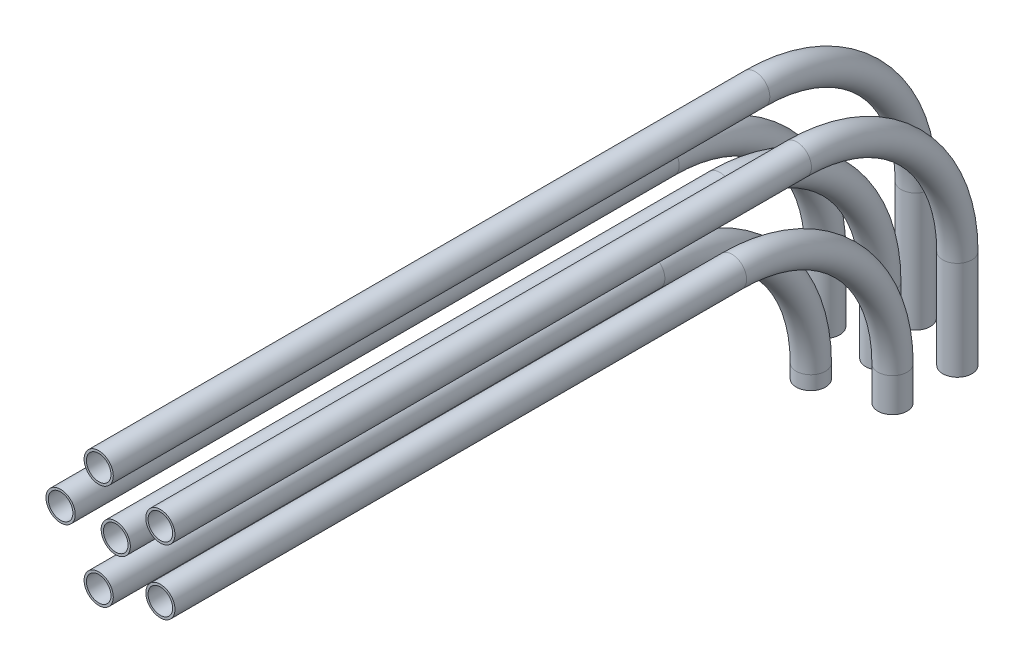
SolidWorks part; units mm, degrees
material "Copper"
ref_plane "Front Plane" through (0, 0, 0) normal (0, 0, 1) x (1, 0, 0)
ref_plane "Top Plane" through (0, 0, 0) normal (0, 1, 0) x (1, 0, 0)
ref_plane "Right Plane" through (0, 0, 0) normal (1, 0, 0) x (0, 0, -1)
sketch "Sketch1" plane through (0, 0, 0) normal (0, 0, 1) x (1, 0, 0)
  line L0 (0, 0) -> (-12, 0) construction
  circle A0 centre (0, 0) radius 3.175
  circle A1 centre (-12, 0) radius 3.175
  circle A2 centre (-3.7082, 11.4127) radius 3.175
  circle A3 centre (9.7082, 7.0534) radius 3.175
  circle A4 centre (9.7082, -7.0534) radius 3.175
  circle A5 centre (-3.7082, -11.4127) radius 3.175
  dimension "D1" = 6.35
  dimension "D2" = 12
  dimension "D3" = 5
extrude "All Tubes Hori" add sketch "Sketch1" along normal blind 120 thin thin type one direction reverse wall 0.5
sketch "Sketch2" plane through (0, 0, 0) normal (0, 0, -1) x (-1, 0, 0)
  line L0 (-6.957, -46.3377) -> (13.6779, -46.3377) construction
  circle A0 centre (3.7082, -11.4127) radius 2.675 construction
  circle A1 centre (3.7082, -11.4127) radius 3.175 construction
  circle A2 centre (3.7082, -11.4127) radius 2.675
  circle A3 centre (3.7082, -11.4127) radius 3.175
  circle A4 centre (-9.7082, -7.0534) radius 3.175 construction
  circle A5 centre (12, 0) radius 3.175 construction
  circle A6 centre (-9.7082, 7.0534) radius 3.175 construction
  dimension "D1" = 31.75
  dimension "D2" = 4.3593
  dimension "D3" = 11.4127
  dimension "D4" = 18.4661
revolve "Tube 1 Revolve" add sketch "Sketch2" angle 90 about L0
sketch "Sketch3" plane through (0, 0, 0) normal (0, 0, -1) x (-1, 0, 0)
  circle A0 centre (-9.7082, -7.0534) radius 2.675 construction
  circle A1 centre (-9.7082, -7.0534) radius 3.175 construction
  circle A2 centre (-9.7082, -7.0534) radius 2.675
  circle A3 centre (-9.7082, -7.0534) radius 3.175
extrude "Tube 2 H Extru" add sketch "Sketch3" along normal blind 4.3593
sketch "Sketch4" plane through (0, 0, -4.3593) normal (0, 0, -1) x (-1, 0, 0)
  line L0 (-15.6235, -41.9784) -> (-3.3734, -41.9784) construction
  circle A0 centre (-9.7082, -7.0534) radius 2.675 construction
  circle A1 centre (-9.7082, -7.0534) radius 3.175 construction
  circle A2 centre (-9.7082, -7.0534) radius 2.675
  circle A3 centre (-9.7082, -7.0534) radius 3.175
  dimension "D1" = 31.75
revolve "Tube 2 Revolve" add sketch "Sketch4" angle 90 about L0
sketch "Sketch5" plane through (0, -41.9784, 0) normal (0, -1, 0) x (1, 0, 0)
  circle A0 centre (9.7082, -39.2843) radius 2.675 construction
  circle A1 centre (9.7082, -39.2843) radius 3.175 construction
  circle A2 centre (9.7082, -39.2843) radius 2.675
  circle A3 centre (9.7082, -39.2843) radius 3.175
extrude "Tube 2 V Extru" add sketch "Sketch5" along normal up to surface (4.3593 mm away) up to face at (-6.3832, -46.3377, -34.925)
sketch "Sketch6" plane through (0, 0, 0) normal (0, 0, -1) x (-1, 0, 0)
  circle A0 centre (12, 0) radius 2.675 construction
  circle A1 centre (12, 0) radius 3.175 construction
  circle A2 centre (0, 0) radius 2.675 construction
  circle A3 centre (0, 0) radius 3.175 construction
  circle A4 centre (12, 0) radius 2.675
  circle A5 centre (12, 0) radius 3.175
  circle A6 centre (0, 0) radius 2.675
  circle A7 centre (0, 0) radius 3.175
extrude "Tube 3 & 4 H Extru" add sketch "Sketch6" along normal blind 11.4127
sketch "Sketch7" plane through (0, 0, -11.4127) normal (0, 0, -1) x (-1, 0, 0)
  line L0 (24.4214, -34.925) -> (-26.0155, -34.925) construction
  circle A0 centre (12, 0) radius 2.675 construction
  circle A1 centre (12, 0) radius 3.175 construction
  circle A2 centre (0, 0) radius 3.175 construction
  circle A3 centre (0, 0) radius 2.675 construction
  circle A4 centre (12, 0) radius 2.675
  circle A5 centre (12, 0) radius 3.175
  circle A6 centre (0, 0) radius 3.175
  circle A7 centre (0, 0) radius 2.675
  dimension "D1" = 31.75
revolve "Tube 3 & 4 Revolve" add sketch "Sketch7" angle 90 about L0
sketch "Sketch8" plane through (0, -34.925, 0) normal (0, -1, 0) x (1, 0, 0)
  circle A0 centre (-12, -46.3377) radius 2.675 construction
  circle A1 centre (-12, -46.3377) radius 3.175 construction
  circle A2 centre (0, -46.3377) radius 3.175 construction
  circle A3 centre (0, -46.3377) radius 2.675 construction
  circle A4 centre (-12, -46.3377) radius 2.675
  circle A5 centre (-12, -46.3377) radius 3.175
  circle A6 centre (0, -46.3377) radius 3.175
  circle A7 centre (0, -46.3377) radius 2.675
extrude "Tube 3 & 4 V Extru" add sketch "Sketch8" along normal up to surface (11.4127 mm away) up to face at (-6.3832, -46.3377, -34.925)
sketch "Sketch9" plane through (0, 0, 0) normal (0, 0, -1) x (-1, 0, 0)
  circle A0 centre (-9.7082, 7.0534) radius 3.175 construction
  circle A1 centre (-9.7082, 7.0534) radius 2.675 construction
  circle A2 centre (-9.7082, 7.0534) radius 3.175
  circle A3 centre (-9.7082, 7.0534) radius 2.675
extrude "Tube 5 H Extru" add sketch "Sketch9" along normal blind 18.4661
sketch "Sketch10" plane through (0, 0, -18.4661) normal (0, 0, -1) x (-1, 0, 0)
  line L0 (-23.4346, -27.8716) -> (-4.6663, -27.8716) construction
  circle A0 centre (-9.7082, 7.0534) radius 3.175 construction
  circle A1 centre (-9.7082, 7.0534) radius 2.675 construction
  circle A2 centre (-9.7082, 7.0534) radius 3.175
  circle A3 centre (-9.7082, 7.0534) radius 2.675
  dimension "D1" = 31.75
revolve "Tube 5 Revolve" add sketch "Sketch10" angle 90 about L0
sketch "Sketch13" plane through (0, -27.8716, 0) normal (0, -1, 0) x (1, 0, 0)
  circle A0 centre (9.7082, -53.3911) radius 3.175 construction
  circle A1 centre (9.7082, -53.3911) radius 2.675 construction
  circle A2 centre (9.7082, -53.3911) radius 3.175
  circle A3 centre (9.7082, -53.3911) radius 2.675
extrude "Tube 5 V Extru" add sketch "Sketch13" along normal up to surface (18.4661 mm away) up to face at (-6.3832, -46.3377, -34.925)
sketch "Sketch11" plane through (0, 0, 0) normal (0, 0, -1) x (-1, 0, 0)
  circle A0 centre (3.7082, 11.4127) radius 3.175 construction
  circle A1 centre (3.7082, 11.4127) radius 2.675 construction
  circle A2 centre (3.7082, 11.4127) radius 3.175
  circle A3 centre (3.7082, 11.4127) radius 2.675
extrude "Tube 6 H Extru" add sketch "Sketch11" along normal blind 22.8254
sketch "Sketch12" plane through (0, 0, -22.8254) normal (0, 0, -1) x (-1, 0, 0)
  line L0 (-21.8503, -23.5123) -> (28.1701, -23.5123) construction
  circle A0 centre (3.7082, 11.4127) radius 3.175 construction
  circle A1 centre (3.7082, 11.4127) radius 2.675 construction
  circle A2 centre (3.7082, 11.4127) radius 3.175
  circle A3 centre (3.7082, 11.4127) radius 2.675
  dimension "D1" = 31.75
revolve "Tube 6 Revolve" add sketch "Sketch12" angle 90 about L0
sketch "Sketch14" plane through (0, -23.5123, 0) normal (0, -1, 0) x (1, 0, 0)
  circle A0 centre (-3.7082, -57.7504) radius 3.175 construction
  circle A1 centre (-3.7082, -57.7504) radius 2.675 construction
  circle A2 centre (-3.7082, -57.7504) radius 3.175
  circle A3 centre (-3.7082, -57.7504) radius 2.675
extrude "Tube 6 V Extru" add sketch "Sketch14" along normal up to surface (22.8254 mm away) up to face at (-6.3832, -46.3377, -34.925)
sketch "Sketch15" plane through (0, -46.3377, 0) normal (0, -1, 0) x (1, 0, 0)
  circle A0 centre (-3.7082, -34.925) radius 2.675 construction
  circle A1 centre (-3.7082, -34.925) radius 3.175 construction
  circle A2 centre (9.7082, -39.2843) radius 2.675 construction
  circle A3 centre (9.7082, -39.2843) radius 3.175 construction
  circle A4 centre (9.7082, -53.3911) radius 2.675 construction
  circle A5 centre (9.7082, -53.3911) radius 3.175 construction
  circle A6 centre (-3.7082, -57.7504) radius 2.675 construction
  circle A7 centre (-3.7082, -57.7504) radius 3.175 construction
  circle A8 centre (-12, -46.3377) radius 2.675 construction
  circle A9 centre (-12, -46.3377) radius 3.175 construction
  circle A10 centre (0, -46.3377) radius 2.675 construction
  circle A11 centre (0, -46.3377) radius 3.175 construction
  circle A12 centre (-3.7082, -34.925) radius 2.675
  circle A13 centre (-3.7082, -34.925) radius 3.175
  circle A14 centre (9.7082, -39.2843) radius 2.675
  circle A15 centre (9.7082, -39.2843) radius 3.175
  circle A16 centre (9.7082, -53.3911) radius 2.675
  circle A17 centre (9.7082, -53.3911) radius 3.175
  circle A18 centre (-3.7082, -57.7504) radius 2.675
  circle A19 centre (-3.7082, -57.7504) radius 3.175
  circle A20 centre (-12, -46.3377) radius 2.675
  circle A21 centre (-12, -46.3377) radius 3.175
  circle A22 centre (0, -46.3377) radius 2.675
  circle A23 centre (0, -46.3377) radius 3.175
extrude "All Tubes Vert" add sketch "Sketch15" along normal blind 3
